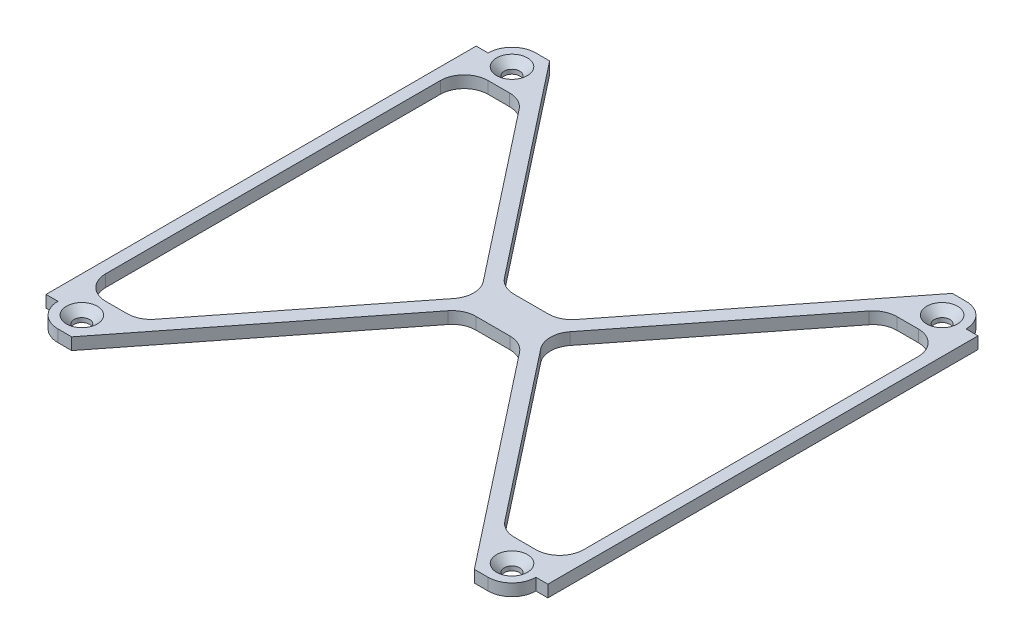
SolidWorks part; units mm, degrees
ref_plane "Front Plane" through (0, 0, 0) normal (0, 0, 1) x (1, 0, 0)
ref_plane "Top Plane" through (0, 0, 0) normal (0, 1, 0) x (1, 0, 0)
ref_plane "Right Plane" through (0, 0, 0) normal (1, 0, 0) x (0, 0, -1)
sketch "Sketch1" plane through (0, 0, 0) normal (0, 1, 0) x (1, 0, 0)
  line L989 (-45, 45) -> (45, 45) construction
  line L1008 (-52.5, -52.5) -> (52.5, -52.5) construction
  line L1009 (-52.5, -52.5) -> (-52.5, 52.5) construction
  line L1028 (-52.5, 52.5) -> (52.5, 52.5) construction
  line L1029 (52.5, -52.5) -> (52.5, 52.5) construction
  line L1030 (-52.5, -52.5) -> (52.5, 52.5) construction
  line L1031 (-52.5, 52.5) -> (52.5, -52.5) construction
  line L1032 (45, 45) -> (45, -45) construction
  line L1033 (45, -45) -> (-45, -45) construction
  line L1034 (-45, -45) -> (-45, 45) construction
  line L1035 (-52.5, 45) -> (-52.5, -45)
  line L1036 (-50, 45) -> (-52.5, 45)
  line L1037 (-50, 40) -> (-50, -40)
  line L1038 (-52.5, 0) -> (-50, 0) construction
  line L1039 (-45, 50) -> (-42.1272, 50)
  line L1040 (-42.1272, 50) -> (-6, 4)
  line L1041 (-6, 4) -> (6, 4)
  line L1042 (-38.088, 40) -> (-6.6731, 0)
  line L1043 (-31.833, 32.0355) -> (-29.4736, 33.8885) construction
  line L1044 (-50, 40) -> (-38.088, 40)
  line L1045 (-6.6731, 0) -> (0, 0) construction
  line L1046 (-55, 0) -> (55, 0) construction
  line L1047 (-50, -40) -> (-38.088, -40)
  line L1048 (-6, -4) -> (6, -4)
  line L1049 (-42.1272, -50) -> (-6, -4)
  line L1050 (-38.088, -40) -> (-6.6731, 0)
  line L1051 (-45, -50) -> (-42.1272, -50)
  line L1052 (-50, -45) -> (-52.5, -45)
  line L1053 (0, -55) -> (0, 55) construction
  line L1054 (45, -50) -> (42.1272, -50)
  line L1055 (50, -45) -> (52.5, -45)
  line L1056 (50, -40) -> (38.088, -40)
  line L1057 (38.088, -40) -> (6.6731, 0)
  line L1058 (42.1272, -50) -> (6, -4)
  line L1059 (38.088, 40) -> (6.6731, 0)
  line L1060 (42.1272, 50) -> (6, 4)
  line L1061 (45, 50) -> (42.1272, 50)
  line L1062 (50, 45) -> (52.5, 45)
  line L1063 (50, 40) -> (38.088, 40)
  line L1064 (50, 40) -> (50, -40)
  line L1065 (52.5, 45) -> (52.5, -45)
  circle A0 centre (-45, 45) radius 1.625
  circle A1 centre (45, 45) radius 1.625
  circle A2 centre (-45, -45) radius 1.625
  circle A3 centre (45, -45) radius 1.625
  arc A4 (-45, 50) -> (-50, 45) centre (-45, 45) ccw
  arc A8 (-45, -50) -> (-50, -45) centre (-45, -45) cw
  arc A9 (45, -50) -> (50, -45) centre (45, -45) ccw
  arc A10 (45, 50) -> (50, 45) centre (45, 45) cw
  point P0 (0, 0)
  point P18 (0, 0)
  point P19 (-29.2526, 33.6071)
  point P26 (-29.4736, 33.8885)
  point P39 (0, 0)
  dimension "D5" = 2.5
  dimension "D6" = 3
  dimension "D8" = 12
  dimension "D7" = 5
  dimension "D2" = 90
  dimension "D3" = 3.25
  dimension "D4" = 5
  dimension "D1" = 105
  dimension "D9" = 8
  dimension "D10" = 128.145
extrude "Boss-Extrude1" add sketch "Sketch1" along normal blind 2.5
fillet "Fillet1" radius 5 6 edges at (6, 1.25, 4) (-6, 1.25, 4) (6, 1.25, -4) (-6, 1.25, -4) (6.6731, 1.25, 0) (-6.6731, 1.25, 0)
fillet "Fillet2" radius 5 8 edges at (50, 1.25, -40) (38.088, 1.25, -40) (38.088, 1.25, 40) (50, 1.25, 40) (-38.088, 1.25, 40) (-50, 1.25, 40) (-38.088, 1.25, -40) (-50, 1.25, -40)
chamfer "Chamfer1" distance 1.6 angle 45 4 edges at (-45, 2.5, 46.625) (45, 2.5, 46.625) (45, 2.5, -43.375) (-45, 2.5, -43.375)
